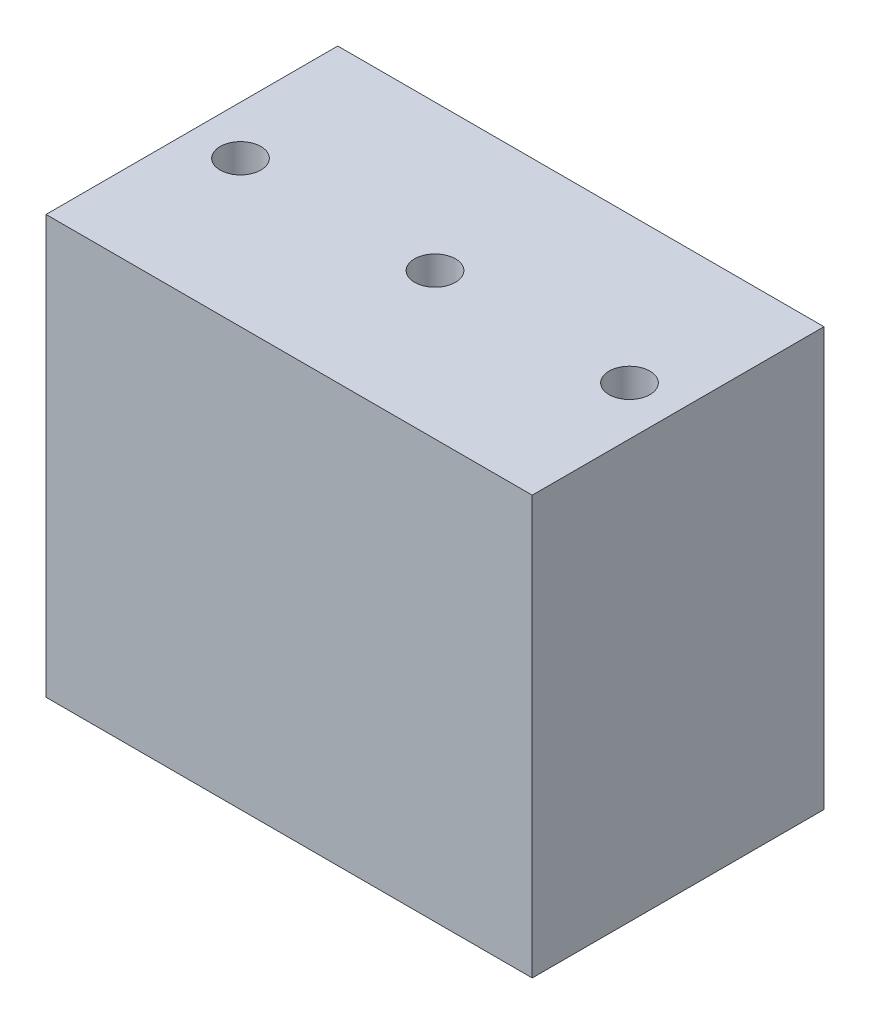
SolidWorks part; units mm, degrees
ref_plane "Front Plane" through (0, 0, 0) normal (0, 0, 1) x (1, 0, 0)
ref_plane "Top Plane" through (0, 0, 0) normal (0, 1, 0) x (1, 0, 0)
ref_plane "Right Plane" through (0, 0, 0) normal (1, 0, 0) x (0, 0, -1)
sketch "Sketch1" plane through (0, 0, 0) normal (0, 1, 0) x (1, 0, 0)
  line L0 (-25, 0) -> (25, 0) construction
  line L1 (-25, 15) -> (25, 15)
  line L2 (-25, 15) -> (-25, -15)
  line L3 (-25, -15) -> (25, -15)
  line L4 (25, 15) -> (25, -15)
  line L5 (-25, 15) -> (25, -15) construction
  line L6 (-25, -15) -> (25, 15) construction
  circle A0 centre (-20, 0) radius 2.1
  circle A1 centre (0, 0) radius 2.1
  circle A2 centre (20, 0) radius 2.1
  point P0 (0, 0)
  dimension "D1" = 4.2
  dimension "D2" = 5
  dimension "D3" = 20
  dimension "D4" = 20
  dimension "D5" = 30
extrude "Boss-Extrude1" add sketch "Sketch1" along normal blind 43
